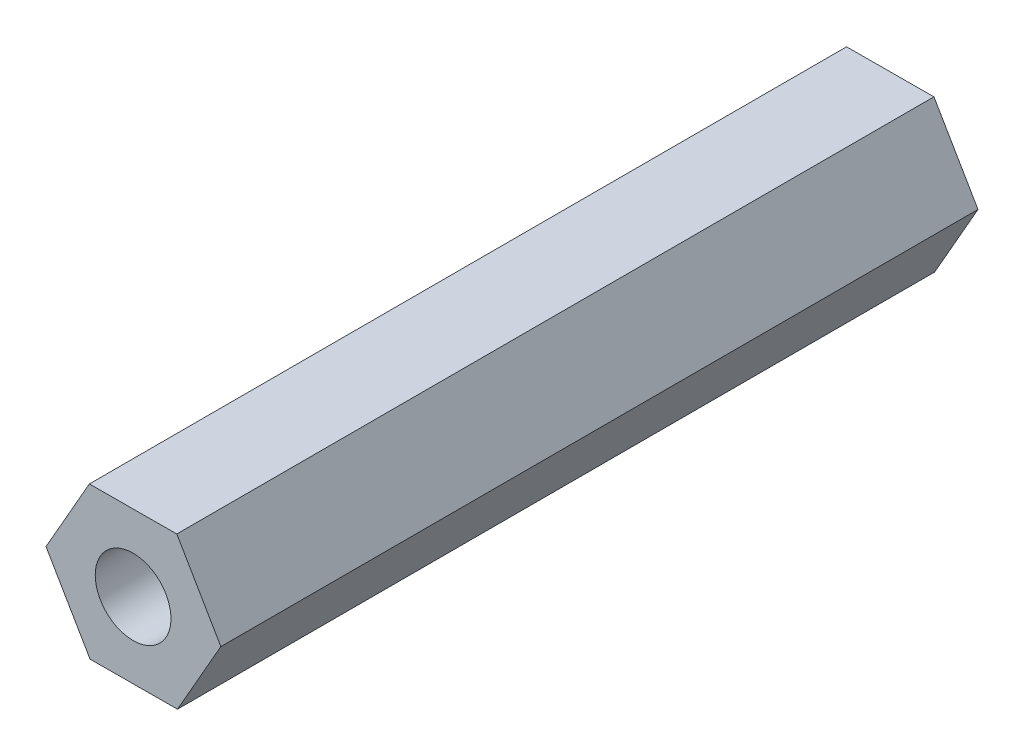
SolidWorks part; units mm, degrees
ref_plane "前视基准面" through (0, 0, 0) normal (0, 0, 1) x (1, 0, 0)
ref_plane "上视基准面" through (0, 0, 0) normal (0, 1, 0) x (1, 0, 0)
ref_plane "右视基准面" through (0, 0, 0) normal (1, 0, 0) x (0, 0, -1)
sketch "草图1" plane through (0, 0, 0) normal (0, 0, 1) x (1, 0, 0)
  line L1 (-66.8574, 15.1689) -> (-65.4252, 17.6753)
  line L2 (-65.4252, 17.6753) -> (-66.8797, 20.1688)
  line L3 (-66.8797, 20.1688) -> (-69.7665, 20.1559)
  line L4 (-69.7665, 20.1559) -> (-71.1986, 17.6495)
  line L5 (-71.1986, 17.6495) -> (-69.7441, 15.156)
  line L6 (-69.7441, 15.156) -> (-66.8574, 15.1689)
  circle A0 centre (-68.3119, 17.6624) radius 2.5 construction
  dimension "D1" = 5
extrude "凸台-拉伸1" add sketch "草图1" along normal blind 25
sketch "草图2" plane through (0, 0, 0) normal (0, 0, -1) x (-1, 0, 0)
  circle A0 centre (68.3231, 17.6495) radius 1.25
  dimension "D1" = 2.5
extrude "切除-拉伸1" cut sketch "草图2" against normal blind 25
